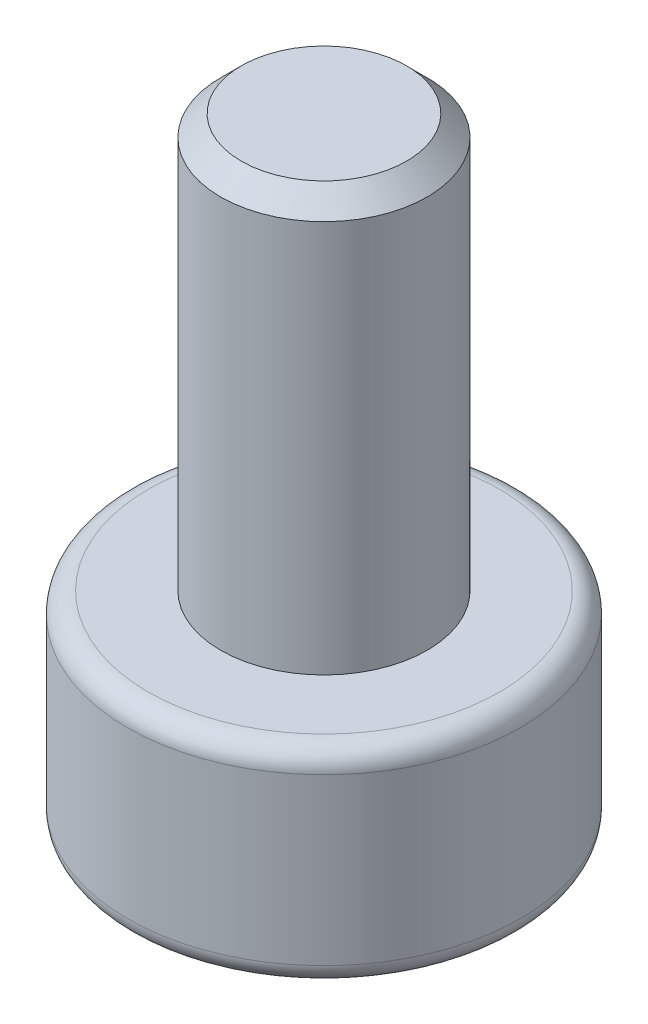
SolidWorks part; units mm, degrees
material "AISI 304"
ref_plane "前视基准面" through (0, 0, 0) normal (0, 0, 1) x (1, 0, 0)
ref_plane "上视基准面" through (0, 0, 0) normal (0, 1, 0) x (1, 0, 0)
ref_plane "右视基准面" through (0, 0, 0) normal (1, 0, 0) x (0, 0, -1)
sketch "草图1" plane through (0, 0, 0) normal (0, 1, 0) x (1, 0, 0)
  circle A0 centre (0, 0) radius 2.85
  dimension "D1" = 5.7
extrude "凸台-拉伸1" add sketch "草图1" along normal blind 3
sketch "草图2" plane through (0, 3, 0) normal (0, 1, 0) x (1, 0, 0)
  circle A0 centre (0, 0) radius 1.5
  dimension "D1" = 3
extrude "凸台-拉伸2" add sketch "草图2" along normal blind 6
sketch "草图3" plane through (0, 0, 0) normal (0, -1, 0) x (1, 0, 0)
  circle A0 centre (0, 0) radius 1.29
  dimension "D1" = 2.58
extrude "切除-拉伸1" cut sketch "草图3" against normal blind 1.3
fillet "圆角1" radius 0.3 2 edges at (0, 3, 2.85) (0, 0, 2.85)
chamfer "倒角1" distance 0.3 angle 45 1 edges at (0, 9, 1.5)
chamfer "倒角2" distance 0.15 angle 45 1 edges at (0, 0, -1.29)
